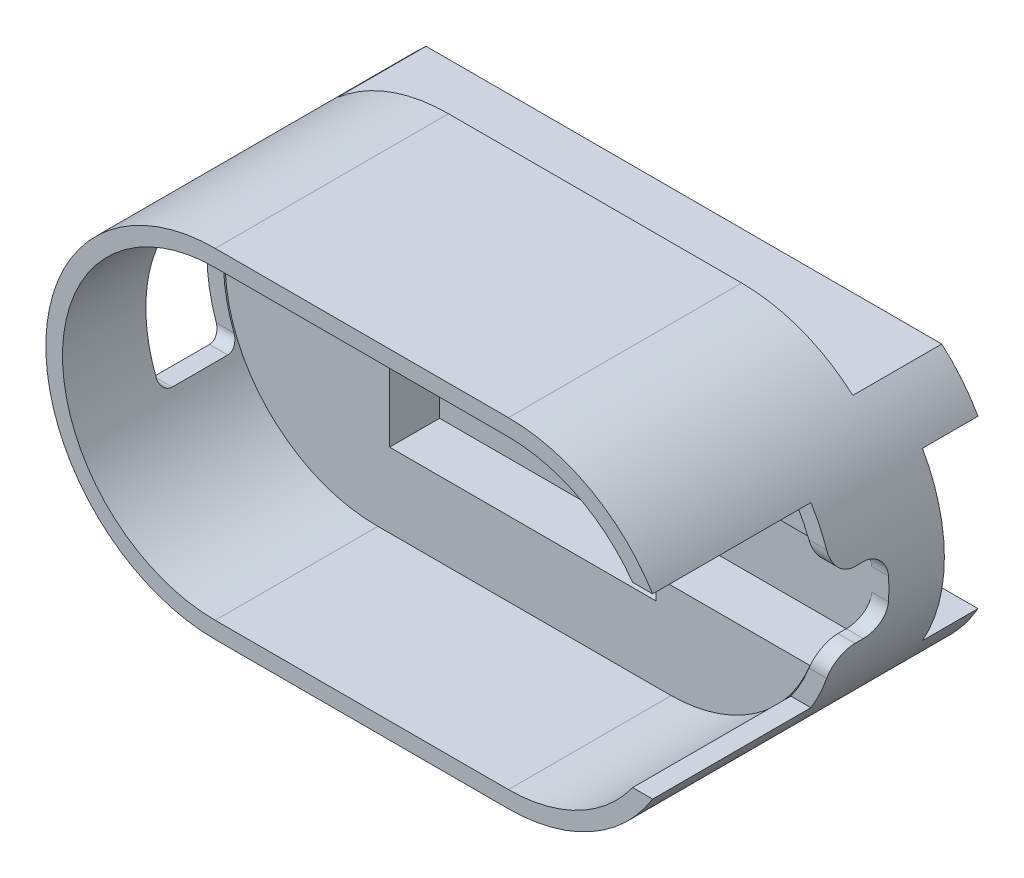
SolidWorks part; units mm, degrees
ref_plane "Front Plane" through (0, 0, 0) normal (0, 0, 1) x (1, 0, 0)
ref_plane "Top Plane" through (0, 0, 0) normal (0, 1, 0) x (1, 0, 0)
ref_plane "Right Plane" through (0, 0, 0) normal (1, 0, 0) x (0, 0, -1)
sketch "Sketch1" plane through (0, 0, 0) normal (0, 0, 1) x (1, 0, 0)
  line L0 (-34.3844, 17.2192) -> (-7.9844, 17.2192)
  line L1 (-34.3844, -10.2808) -> (-7.9844, -10.2808)
  line L2 (-34.3844, 18.7192) -> (-7.9844, 18.7192)
  line L3 (-34.3844, -11.7808) -> (-7.9844, -11.7808)
  arc A0 (-34.3844, 17.2192) -> (-34.3844, -10.2808) centre (-34.3844, 3.4692) ccw
  arc A1 (-7.9844, -10.2808) -> (-7.9844, 17.2192) centre (-7.9844, 3.4692) ccw
  arc A2 (-7.9844, -11.7808) -> (-7.9844, 18.7192) centre (-7.9844, 3.4692) ccw
  arc A3 (-34.3844, 18.7192) -> (-34.3844, -11.7808) centre (-34.3844, 3.4692) ccw
  point P8 (-48.1344, 3.4692)
  point P9 (5.7656, 3.4692)
  dimension "D1" = 27.5
  dimension "D2" = 53.9
  dimension "D3" = 1.5
extrude "Boss-Extrude1" add sketch "Sketch1" along normal blind 19
sketch "Sketch2" plane through (0, 0, 0) normal (0, 0, -1) x (-1, 0, 0)
  line L0 (34.3844, -11.7808) -> (7.9844, -11.7808)
  line L1 (34.3844, 18.7192) -> (7.9844, 18.7192)
  arc A0 (7.9844, 18.7192) -> (7.9844, -11.7808) centre (7.9844, 3.4692) ccw
  arc A1 (34.3844, -11.7808) -> (34.3844, 18.7192) centre (34.3844, 3.4692) ccw
  arc M5 (34.3844, 17.2192) -> (34.3844, -10.2808) centre (34.3844, 3.4692) cw
  line M6 (34.3844, -10.2808) -> (7.9844, -10.2808)
  arc M7 (7.9844, -10.2808) -> (7.9844, 17.2192) centre (7.9844, 3.4692) cw
  line M8 (7.9844, 17.2192) -> (34.3844, 17.2192)
extrude "Boss-Extrude2" add sketch "Sketch2" along normal blind 2 separate body contours A1 A0 M8 M7 M6 | A1 A0 M6 | A1 A0 M8 M6 M5 | A0 A1 | A1 A0 M8
sketch "Sketch3" plane through (0, 0, 0) normal (0, 0, 1) x (1, 0, 0)
  line L0 (-21.1844, 17.2192) -> (-21.1844, -10.2808) construction
  line L1 (-7.9844, 17.2192) -> (-34.3844, 17.2192) construction
  line L2 (-34.3844, -10.2808) -> (-7.9844, -10.2808) construction
  line L3 (-9.1844, 3.4692) -> (4.8328, 3.4692) construction
  line L4 (-33.1844, -3.4308) -> (-9.1844, -3.4308)
  line L5 (-33.1844, -3.4308) -> (-33.1844, 10.3692)
  line L6 (-33.1844, 10.3692) -> (-9.1844, 10.3692)
  line L7 (-9.1844, -3.4308) -> (-9.1844, 10.3692)
  line L8 (-33.1844, -3.4308) -> (-9.1844, 10.3692) construction
  line L9 (-33.1844, 10.3692) -> (-9.1844, -3.4308) construction
  line L10 (-9.1844, -1.5308) -> (4.6632, -1.5308)
  line L11 (-9.1844, 8.4692) -> (4.6632, 8.4692)
  line L12 (-34.3844, 17.0693) -> (-7.9844, 17.0693)
  line L13 (-7.9844, -10.1309) -> (-34.3844, -10.1309)
  line L14 (-9.1844, -1.5308) -> (4.8328, -1.5308) construction
  line L15 (-9.1844, 8.4692) -> (4.8328, 8.4692) construction
  arc A0 (-19.7042, 10.3692) -> (-19.7042, -3.4308) centre (-7.9844, 3.4692) ccw
  arc A1 (-34.3844, 17.0693) -> (-34.3844, -10.1309) centre (-34.3844, 3.4692) ccw
  arc A2 (-7.9844, -10.1309) -> (-7.9844, 17.0693) centre (-7.9844, 3.4692) ccw
  arc A3 (-22.6647, -3.4308) -> (-21.1844, 6.7437) centre (-34.3844, 3.4692) ccw
  point P6 (-21.1844, 3.4692)
  dimension "D1" = 13.8
  dimension "D2" = 24
  dimension "D3" = 5
  dimension "D4" = 5
extrude "Boss-Extrude3" add sketch "Sketch3" along normal blind 4.5 contours L11 A2 L12 A1 L13 L10 L7 L4 L5 L6
sketch "Sketch4" plane through (-9.1844, 0, 0) normal (-1, 0, 0) x (0, 0, 1)
  line L0 (4.5, -1.5308) -> (4.5, 8.4692) construction
  line L1 (4.5, 3.4692) -> (9.0795, 3.4692) construction
  line L2 (0, -3.4308) -> (0, -1.5308) construction
  line L3 (4.75, 11.4692) -> (19, 11.4692)
  line L4 (4.75, 11.4692) -> (4.75, -4.5308)
  line L5 (4.75, -4.5308) -> (19, -4.5308)
  line L6 (19, 11.4692) -> (19, -4.5308)
  line L7 (4.75, 11.4692) -> (19, -4.5308) construction
  line L8 (4.75, -4.5308) -> (19, 11.4692) construction
  line L9 (0, 6.4692) -> (4.75, 6.4692)
  line L10 (0, 6.4692) -> (0, 0.4692)
  line L11 (0, 0.4692) -> (4.75, 0.4692)
  line L12 (4.75, 6.4692) -> (4.75, 0.4692)
  line L13 (0, 6.4692) -> (4.75, 0.4692) construction
  line L14 (0, 0.4692) -> (4.75, 6.4692) construction
  line L15 (19, -10.2808) -> (19, 17.2192) construction
  point P6 (11.875, 3.4692)
  point P11 (2.375, 3.4692)
  dimension "D1" = 16
  dimension "D3" = 0.5
  dimension "D4" = 6
extrude "Cut-Extrude1" cut sketch "Sketch4" against normal through all contours L10 L11 L4 L9 | L6 L3 L4 L5
sketch "Sketch5" plane through (-33.1844, 0, 0) normal (1, 0, 0) x (0, 0, -1)
  line L0 (-4.5, 3.4692) -> (-8.318, 3.4692) construction
  line L1 (-4.5, -3.4308) -> (-4.5, 10.3692) construction
  line L3 (-4.5, -2.5308) -> (-11.5, -2.5308)
  line L4 (-4.5, -2.5308) -> (-4.5, 9.4692)
  line L5 (-4.5, 9.4692) -> (-11.5, 9.4692)
  line L6 (-11.5, -2.5308) -> (-11.5, 9.4692)
  line L7 (-4.5, -2.5308) -> (-11.5, 9.4692) construction
  line L8 (-4.5, 9.4692) -> (-11.5, -2.5308) construction
  point P4 (-8, 3.4692)
  dimension "D1" = 12
  dimension "D2" = 7
extrude "Cut-Extrude2" cut sketch "Sketch5" against normal through all
fillet "Fillet1" radius 1 4 edges at (-47.5804, 9.4692, 4.5) (-47.5804, -2.5308, 4.5) (-47.5804, -2.5308, 11.5) (-47.5804, 9.4692, 11.5)
sketch "Sketch6" plane through (0, 0, -2) normal (0, 0, -1) x (-1, 0, 0)
  line L0 (49.6344, 3.4692) -> (-7.2656, 3.4692) construction
  line L1 (47.6627, 10.9692) -> (-5.2938, 10.9692)
  line L2 (47.6627, -4.0308) -> (-5.2938, -4.0308)
  line L3 (43.1201, -9.0308) -> (-0.7513, -9.0308)
  line L4 (43.1201, 15.9692) -> (-0.7513, 15.9692)
  line L5 (49.6344, -9.0308) -> (-7.2656, -9.0308) construction
  line L6 (49.6344, -4.0308) -> (-7.2656, -4.0308) construction
  line L7 (49.6344, 15.9692) -> (-7.2656, 15.9692) construction
  line L8 (49.6344, 10.9692) -> (-7.2656, 10.9692) construction
  arc A0 (34.3844, -11.7808) -> (34.3844, 18.7192) centre (34.3844, 3.4692) ccw construction
  arc A1 (7.9844, 18.7192) -> (7.9844, -11.7808) centre (7.9844, 3.4692) ccw construction
  arc A2 (43.1201, -9.0308) -> (43.1201, 15.9692) centre (34.3844, 3.4692) ccw
  arc A3 (21.1844, -4.1677) -> (21.1844, 11.1061) centre (7.9844, 3.4692) ccw
  arc A4 (-0.7513, 15.9692) -> (-0.7513, -9.0308) centre (7.9844, 3.4692) ccw
  arc A5 (21.1844, 11.1061) -> (21.1844, -4.1677) centre (34.3844, 3.4692) ccw
  circle A6 centre (21.1844, 3.4692) radius 1.25
  arc M5 (34.3844, -11.7808) -> (34.3844, 18.7192) centre (34.3844, 3.4692) ccw
  arc M7 (7.9844, 18.7192) -> (7.9844, -11.7808) centre (7.9844, 3.4692) ccw
  dimension "D5" = 2.5
  dimension "D1" = 7.5
  dimension "D2" = 7.5
  dimension "D3" = 5
  dimension "D4" = 5
extrude "Boss-Extrude4" add sketch "Sketch6" along normal blind 3 contours A3 L2 L1 M5 | L1 A5 L2 A3 | A5 L1 L2 M7
sketch "Sketch9" plane through (0, 0, -2) normal (0, 0, -1) x (-1, 0, 0)
  circle A0 centre (21.1844, 3.4692) radius 1.2524
  dimension "D1" = 2.5049
sketch "Sketch10" plane through (0, 0, -2) normal (0, 0, -1) x (-1, 0, 0)
  line L0 (-5.2938, -4.0308) -> (47.6627, -4.0308)
  line L1 (47.6627, 10.9692) -> (-5.2938, 10.9692)
  line L2 (44.4001, 14.9692) -> (-2.0312, 14.9692)
  line L3 (-2.0312, -8.0308) -> (44.4001, -8.0308)
  line L4 (-5.2938, -8.0308) -> (47.6627, -8.0308) construction
  line L5 (47.6627, 14.9692) -> (-5.2938, 14.9692) construction
  line L6 (47.6627, 10.9692) -> (-5.2938, 10.9692) construction
  arc A0 (44.4001, -8.0308) -> (47.6627, -4.0308) centre (34.3844, 3.4692) ccw
  arc A1 (47.6627, 10.9692) -> (44.4001, 14.9692) centre (34.3844, 3.4692) ccw
  arc A2 (-2.0312, 14.9692) -> (-5.2938, 10.9692) centre (7.9844, 3.4692) ccw
  arc A3 (-5.2938, -4.0308) -> (-2.0312, -8.0308) centre (7.9844, 3.4692) ccw
  line M2 (-5.2938, 10.9692) -> (47.6627, 10.9692)
  arc M3 (47.6627, 10.9692) -> (34.3844, 18.7192) centre (34.3844, 3.4692) ccw
  arc M5 (7.9844, 18.7192) -> (-5.2938, 10.9692) centre (7.9844, 3.4692) ccw
  dimension "D1" = 4
  dimension "D2" = 4
extrude "Boss-Extrude7" add sketch "Sketch10" along direction (0, 0, -1) on the side of the normal blind 8 contours L0 A3 L3 A0 | L2 M3 M5 M2
fillet "Fillet2" radius 2 4 edges at (6.2009, 0.4692, 0) (6.2009, 6.4692, 0) (6.2009, 6.4692, 4.75) (6.2009, 0.4692, 4.75)
extrude "Cut-Extrude3" cut sketch "Sketch9" against normal blind 10
sketch "Sketch13" plane through (0, 0, -5) normal (0, 0, -1) x (-1, 0, 0)
  line L1 (17.9513, 3.4692) -> (19.5679, 0.6692)
  line L2 (19.5679, 0.6692) -> (22.801, 0.6692)
  line L3 (22.801, 0.6692) -> (24.4176, 3.4692)
  line L4 (24.4176, 3.4692) -> (22.801, 6.2692)
  line L5 (22.801, 6.2692) -> (19.5679, 6.2692)
  line L6 (19.5679, 6.2692) -> (17.9513, 3.4692)
  circle A0 centre (21.1844, 3.4692) radius 2.8 construction
  dimension "D1" = 5.6
extrude "Cut-Extrude6" cut sketch "Sketch13" against normal blind 2.1 from offset 1.5
